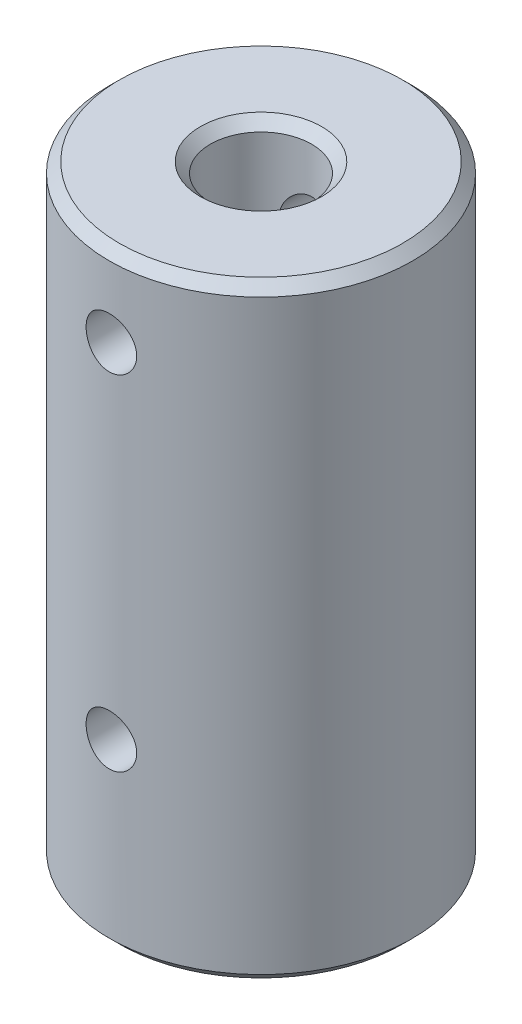
SolidWorks part; units mm, degrees
material "6061-O (SS)"
ref_plane "前视基准面" through (0, 0, 0) normal (0, 0, 1) x (1, 0, 0)
ref_plane "上视基准面" through (0, 0, 0) normal (0, 1, 0) x (1, 0, 0)
ref_plane "右视基准面" through (0, 0, 0) normal (1, 0, 0) x (0, 0, -1)
sketch "草图1" plane through (0, 0, 0) normal (0, 0, 1) x (1, 0, 0)
  line L0 (0, 0) -> (0, 30) construction
  line L1 (5, 0) -> (5, 20)
  line L2 (5, 20) -> (2.5, 20)
  line L3 (2.5, 20) -> (2.5, 30)
  line L4 (2.5, 30) -> (7.5, 30)
  line L5 (7.5, 30) -> (7.5, 0)
  line L6 (7.5, 0) -> (5, 0)
  dimension "D1" = 10
  dimension "D2" = 5
  dimension "D3" = 15
  dimension "D4" = 20
  dimension "D5" = 30
revolve "旋转1" add sketch "草图1" angle 360 about L0
chamfer "倒角1" distance 0.5 angle 45 4 edges at (0, 0, -5) (0, 0, -7.5) (0, 30, -7.5) (0, 30, -2.5)
ref_plane "基准面1" through (0, 0, 7.5) normal (0, 0, 1) x (1, 0, 0)
hole_wizard "M3 螺纹孔2" positions "草图3" profile "草图4" tap size "M3" standard "GB" end condition through all
sketch "草图3" plane through (0, 0, 7.5) normal (0, 0, 1) x (1, 0, 0)
  line L0 (0, 26) -> (0, 9)
  point P0 (0, 26)
  point P2 (0, 9)
  dimension "D1" = 9
  dimension "D2" = 17
sketch "草图4" plane through (0, 26, 7.5) normal (1, 0, 0) x (0, -1, 0)
  line L0 (0, 0) -> (0, 15)
  line L1 (0, 15) -> (1.25, 15)
  line L2 (1.25, 15) -> (1.25, 0)
  line L5 (1.25, 0) -> (0, 0)
  line L11 (0, -6.35) -> (0, 107.95) construction
  dimension "通孔螺纹孔钻头直径" = 2.5
  dimension "通孔螺纹孔钻头深度" = 15
cosmetic thread "孔螺蚊线5" parameters "D2"=3
cosmetic thread "孔螺蚊线6" parameters "D2"=3
